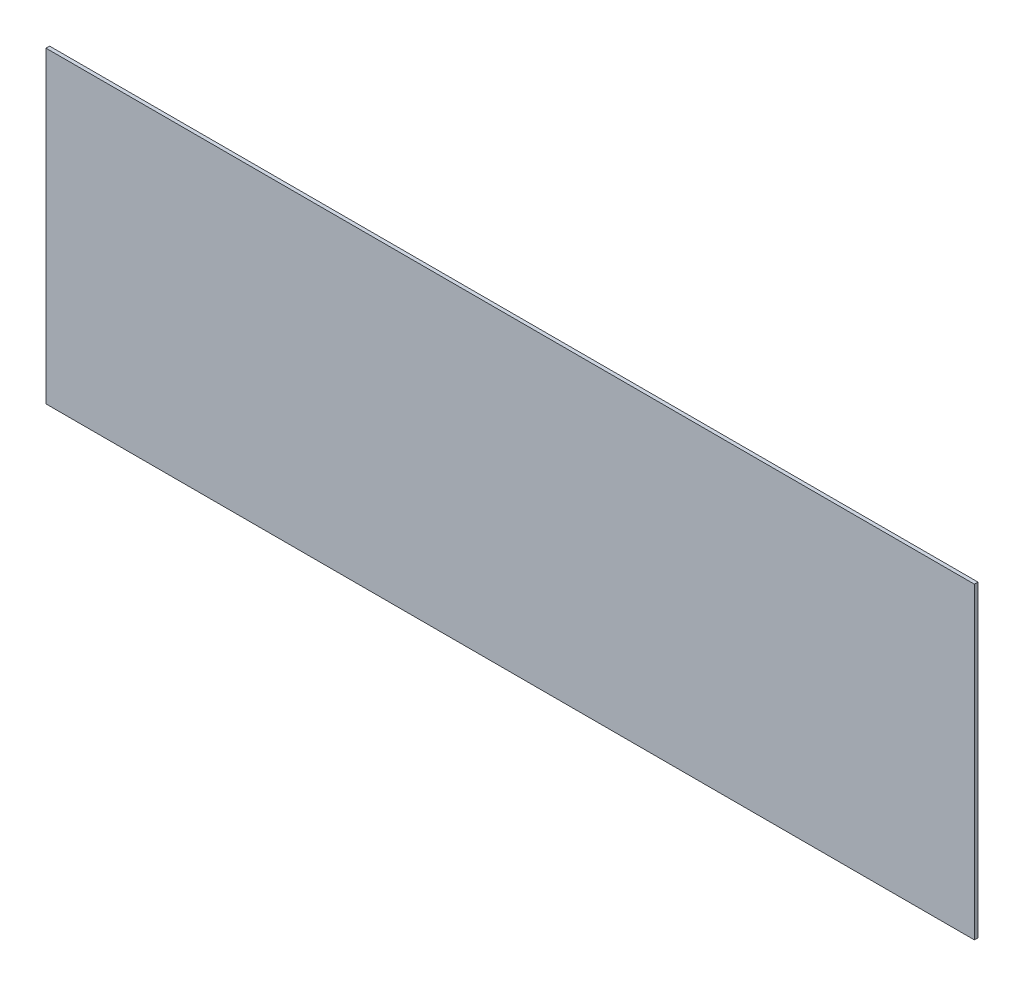
SolidWorks part; units mm, degrees
material "PLA"
ref_plane "Front Plane" through (0, 0, 0) normal (0, 0, 1) x (1, 0, 0)
ref_plane "Top Plane" through (0, 0, 0) normal (0, 1, 0) x (1, 0, 0)
ref_plane "Right Plane" through (0, 0, 0) normal (1, 0, 0) x (0, 0, -1)
sketch "Sketch1" plane through (0, 0, 0) normal (0, 0, 1) x (1, 0, 0)
  line L1 (189.8842, 126.9344) -> (-323.2858, 126.9344)
  line L2 (189.8842, 126.9344) -> (189.8842, -43.3656)
  line L3 (189.8842, -43.3656) -> (-323.2858, -43.3656)
  line L4 (-323.2858, 126.9344) -> (-323.2858, -43.3656)
  dimension "D1" = 513.17
  dimension "D2" = 170.3
extrude "Boss-Extrude1" add sketch "Sketch1" along normal blind 2
